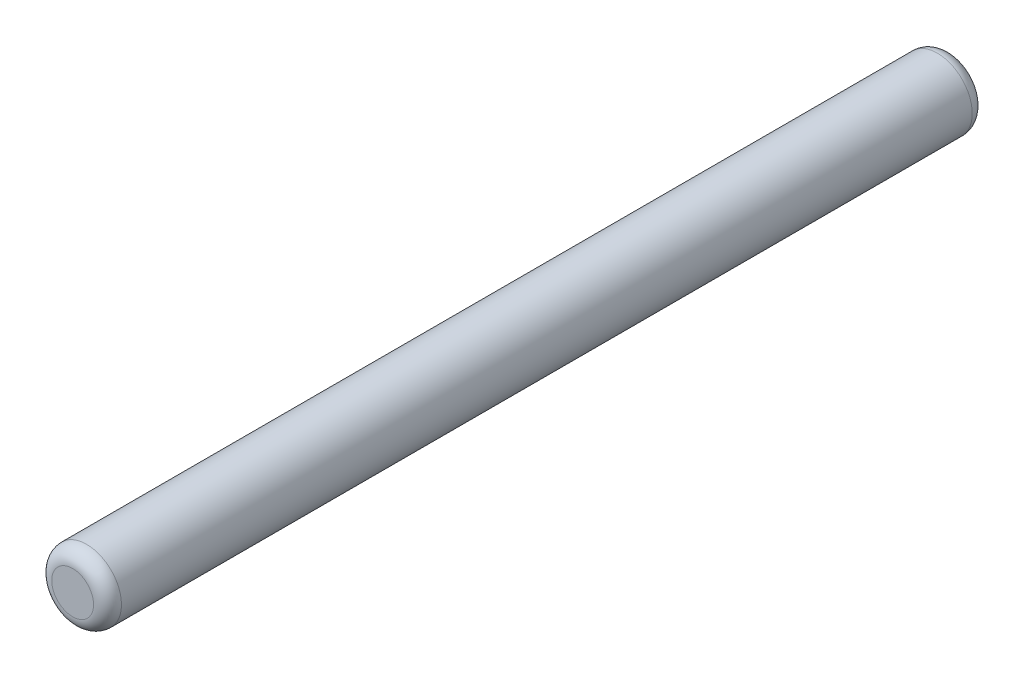
SolidWorks part; units mm, degrees
ref_plane "Front Plane" through (0, 0, 0) normal (0, 0, 1) x (1, 0, 0)
ref_plane "Top Plane" through (0, 0, 0) normal (0, 1, 0) x (1, 0, 0)
ref_plane "Right Plane" through (0, 0, 0) normal (1, 0, 0) x (0, 0, -1)
sketch "Sketch1" plane through (0, 0, 0) normal (0, 0, 1) x (1, 0, 0)
  circle A0 centre (0, 0) radius 1.5875
extrude "Boss-Extrude1" add sketch "Sketch1" along normal blind 40.005
fillet "Fillet2" radius 0.635 2 edges at (1.5875, 0, 0) (1.5875, 0, 40.005)
